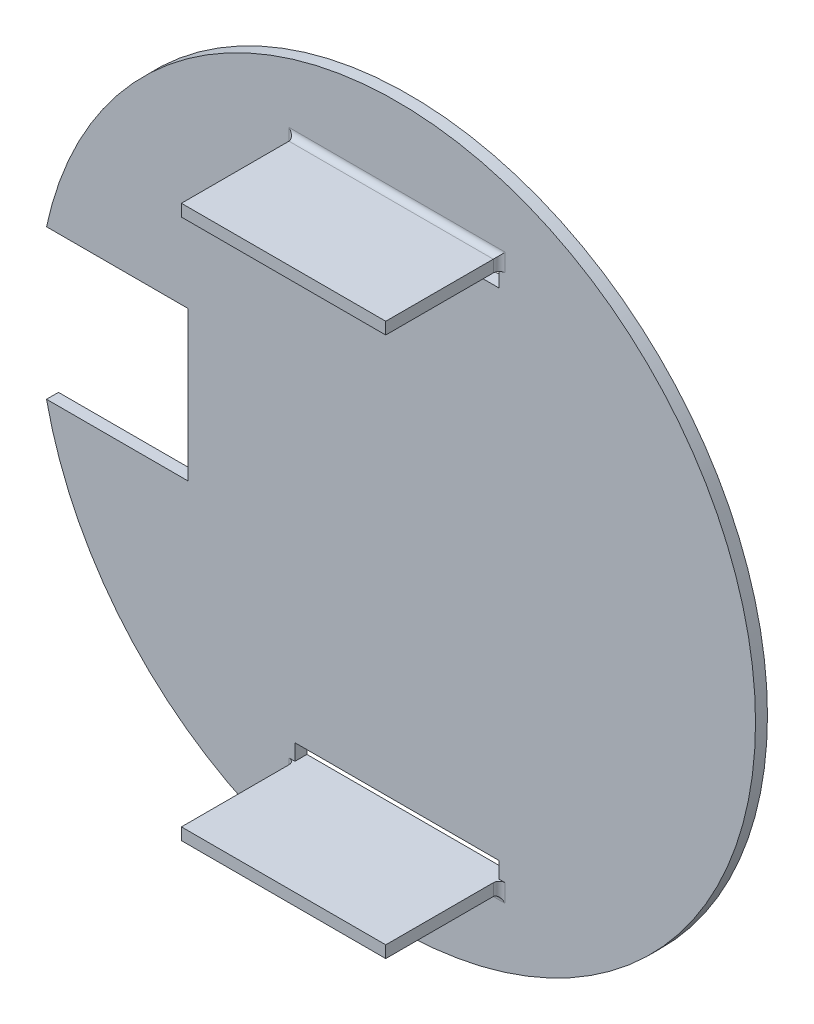
SolidWorks part; units mm, degrees
ref_plane "Alzado" through (0, 0, 0) normal (0, 0, 1) x (1, 0, 0)
ref_plane "Planta" through (0, 0, 0) normal (0, 1, 0) x (1, 0, 0)
ref_plane "Vista lateral" through (0, 0, 0) normal (1, 0, 0) x (0, 0, -1)
sketch "Croquis1" plane through (0, 0, 0) normal (0, 0, 1) x (1, 0, 0)
  line L0 (-35, 0) -> (0, 0) construction
  line L1 (-58.6835, -12.5) -> (-35, -12.5)
  line L2 (-60, -12.5) -> (-60, 12.5) construction
  line L3 (-58.6835, 12.5) -> (-35, 12.5)
  line L4 (-35, -12.5) -> (-35, 12.5)
  line L5 (-17.1, 44.2) -> (17.1, 44.2)
  line L6 (-17.1, 44.2) -> (-17.1, 41.5)
  line L7 (-17.1, 41.5) -> (17.1, 41.5)
  line L8 (17.1, 44.2) -> (17.1, 41.5)
  line L9 (-17.1, -41.5) -> (17.1, -41.5)
  line L10 (17.1, -44.2) -> (17.1, -41.5)
  line L11 (-17.1, -44.2) -> (17.1, -44.2)
  line L12 (-17.1, -44.2) -> (-17.1, -41.5)
  arc A0 (-58.6835, -12.5) -> (-58.6835, 12.5) centre (0, 0) ccw
  point P7 (0, 41.5)
  point P8 (-35, 0)
  point P9 (-60, 0)
  dimension "D1" = 120
  dimension "D2" = 25
  dimension "D3" = 25
  dimension "D4" = 50
  dimension "D5" = 34.2
  dimension "D6" = 2.7
  dimension "D7" = 41.5
extrude "Saliente-Extruir1" add sketch "Croquis1" along normal blind 2
sketch "Croquis2" plane through (0, 0, 2) normal (0, 0, 1) x (1, 0, 0)
  line L0 (17.1, 41.5) -> (17.1, 44.2) construction
  line L1 (-17.1, 44.2) -> (17.1, 44.2)
  line L2 (-17.1, 44.2) -> (-17.1, 46.2)
  line L3 (-17.1, 46.2) -> (17.1, 46.2)
  line L4 (17.1, 44.2) -> (17.1, 46.2)
  line L5 (0, 0) -> (-35, 0) construction
  line L6 (-35, 12.5) -> (-35, -12.5) construction
  line L7 (17.1, -44.2) -> (17.1, -46.2)
  line L8 (-17.1, -44.2) -> (-17.1, -46.2)
  line L9 (-17.1, -44.2) -> (17.1, -44.2)
  line L10 (-17.1, -46.2) -> (17.1, -46.2)
  dimension "D1" = 2
extrude "Saliente-Extruir2" add sketch "Croquis2" along normal blind 19
fillet "Redondeo1" radius 1 6 edges at (17.1, -45.2, 2) (-17.1, -45.2, 2) (0, -46.2, 2) (-17.1, 45.2, 2) (17.1, 45.2, 2) (0, 46.2, 2)
